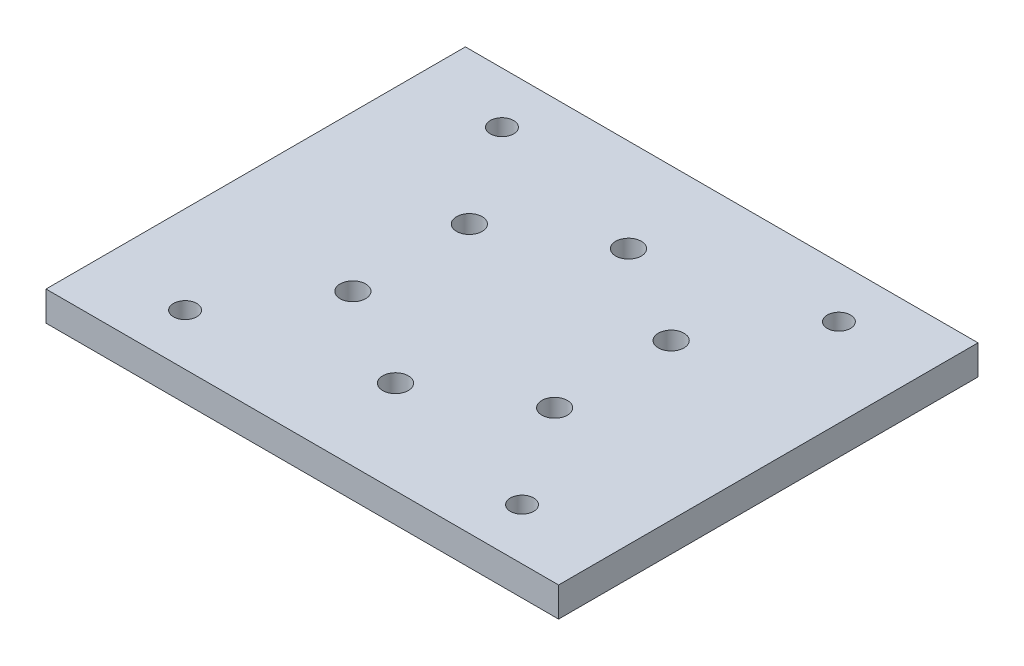
SolidWorks part; units mm, degrees
material "6061 Alloy"
ref_plane "Front Plane" through (0, 0, 0) normal (0, 0, 1) x (1, 0, 0)
ref_plane "Top Plane" through (0, 0, 0) normal (0, 1, 0) x (1, 0, 0)
ref_plane "Right Plane" through (0, 0, 0) normal (1, 0, 0) x (0, 0, -1)
sketch "Sketch2" plane through (0, 0, 0) normal (0, 1, 0) x (1, 0, 0)
  line L0 (0, 0) -> (0, 90)
  line L1 (0, 90) -> (110, 90)
  line L2 (110, 90) -> (110, 0)
  line L3 (110, 0) -> (0, 0)
  dimension "D1" = 110
  dimension "D2" = 90
extrude "Boss-Extrude1" add sketch "Sketch2" along normal blind 6.35
sketch "Sketch3" plane through (0, 6.35, 0) normal (0, 1, 0) x (1, 0, 0)
  line L1 (110, 90) -> (0, 90) construction
  line L2 (0, 0) -> (110, 0) construction
  line L4 (55, 90) -> (55, 0) construction
  line L5 (0, 45) -> (55, 45) construction
  line L6 (55, 45) -> (110, 45) construction
  line L7 (0, 90) -> (0, 0) construction
  circle A0 centre (18.85, 79) radius 2.5
  circle A1 centre (18.85, 11) radius 2.5
  circle A2 centre (91.15, 11) radius 2.5
  circle A3 centre (91.15, 79) radius 2.5
  dimension "D4" = 5
  dimension "D3" = 11
  dimension "D2" = 18.85
extrude "Mounting Holes" cut sketch "Sketch3" against normal through all
sketch "Sketch4" plane through (0, 6.35, 0) normal (0, 1, 0) x (1, 0, 0)
  line L0 (18.85, 79) -> (91.15, 11) construction
  circle A0 centre (55, 45) radius 25 construction
  circle A1 centre (55, 70) radius 2.75
  circle A2 centre (76.6506, 57.5) radius 2.75
  circle A3 centre (76.6506, 32.5) radius 2.75
  circle A4 centre (55, 20) radius 2.75
  circle A5 centre (33.3494, 32.5) radius 2.75
  circle A6 centre (33.3494, 57.5) radius 2.75
  point P20 (55, 45)
  dimension "D1" = 50
  dimension "D2" = 5.5
  dimension "D3" = 6
extrude "Cut-Extrude1" cut sketch "Sketch4" against normal through all
sketch "Sketch5" plane through (0, 6.35, 0) normal (0, 1, 0) x (1, 0, 0)
  circle A0 centre (55, 45) radius 25 construction
  circle A1 centre (55, 20) radius 2.75 construction
  circle A2 centre (55, 20) radius 2.75 construction
  circle A3 centre (33.3494, 32.5) radius 2.75 construction
  circle A4 centre (33.3494, 32.5) radius 2.75 construction
  circle A5 centre (33.3494, 57.5) radius 2.75 construction
  circle A6 centre (33.3494, 57.5) radius 2.75 construction
ref_plane "Plane2" through (55, 0, 0) normal (1, 0, 0) x (0, 0, -1)
equation "\"L1L\"=500"
equation "\"L1Thick\"=6.35"
equation "\"Harm-Drive-Outer\"=74.5"
equation "\"L1-Spacing\"=100"
equation "\"L-Bracket-HoleToWall\"=12.5"
equation "\"D3@Sketch3\"=\"L-Bracket-HoleToSide\""
equation "\"L-Bracket-HoleToSide\"=11"
equation "\"Bracket-Hole-D\"=6.8"
equation "\"L1-Spacing\"=115.65"
equation "\"D2@Sketch3\"=\"L-Bracket-HoleToWall\"+\"L1Thick\""
